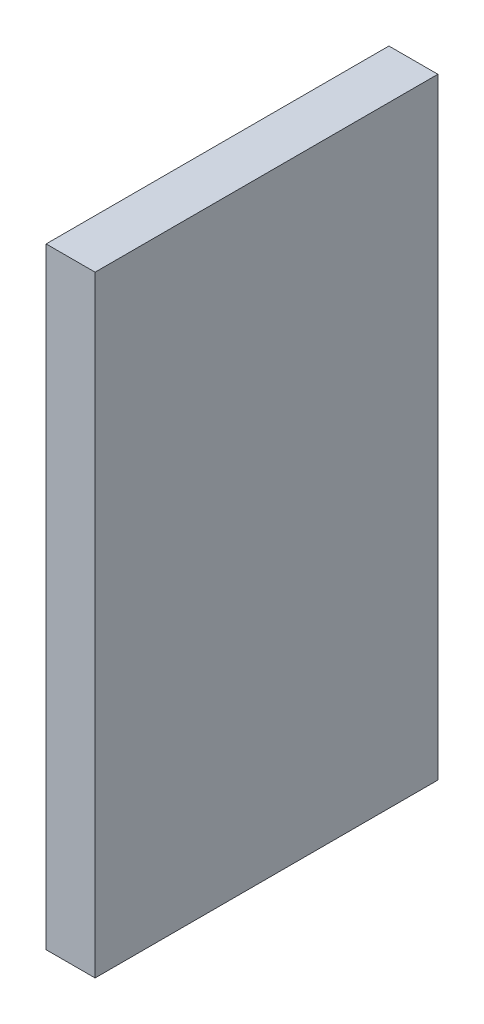
SolidWorks part; units mm, degrees
ref_plane "Front Plane" through (0, 0, 0) normal (0, 0, 1) x (1, 0, 0)
ref_plane "Top Plane" through (0, 0, 0) normal (0, 1, 0) x (1, 0, 0)
ref_plane "Right Plane" through (0, 0, 0) normal (1, 0, 0) x (0, 0, -1)
sketch "Sketch1" plane through (14.3621, 0, 0) normal (1, 0, 0) x (0, 0, -1)
  line L1 (-758.8739, 286.7576) -> (-723.8585, 286.7576)
  line L2 (-758.8739, 286.7576) -> (-758.8739, 224.3176)
  line L3 (-758.8739, 224.3176) -> (-723.8585, 224.3176)
  line L4 (-723.8585, 286.7576) -> (-723.8585, 224.3176)
extrude "Boss-Extrude1" add sketch "Sketch1" along normal blind 5
